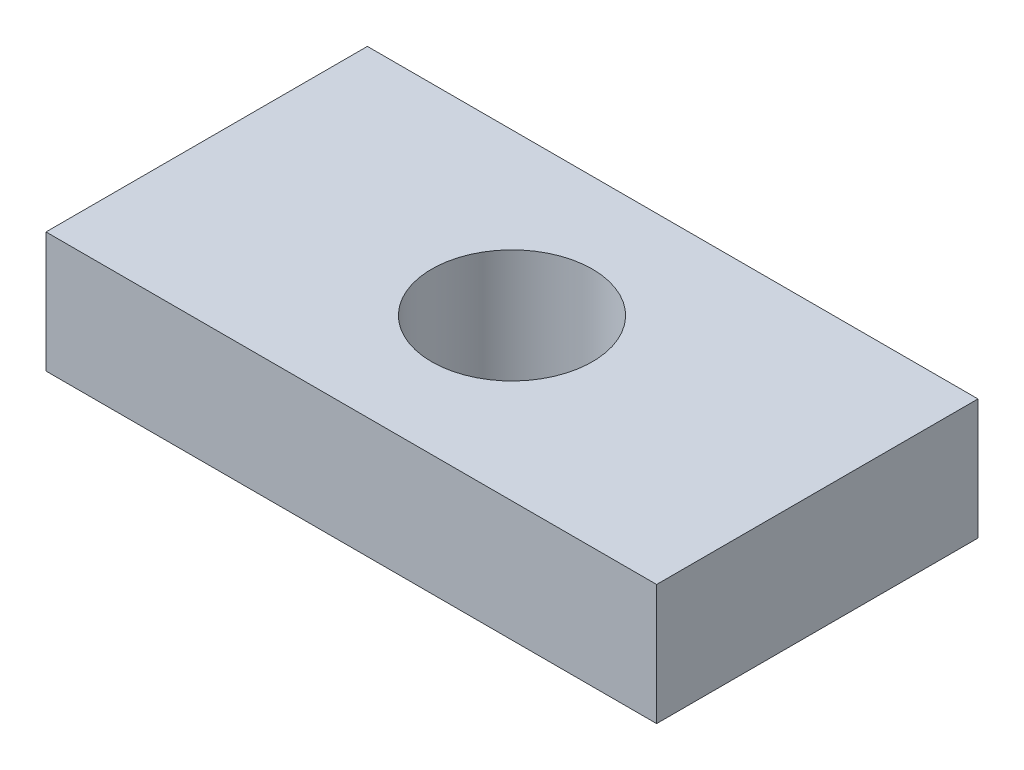
SolidWorks part; units mm, degrees
ref_plane "Front Plane" through (0, 0, 0) normal (0, 0, 1) x (1, 0, 0)
ref_plane "Top Plane" through (0, 0, 0) normal (0, 1, 0) x (1, 0, 0)
ref_plane "Right Plane" through (0, 0, 0) normal (1, 0, 0) x (0, 0, -1)
sketch "Sketch1" plane through (0, 0, 0) normal (0, 1, 0) x (1, 0, 0)
  line L1 (-38, 20) -> (38, 20)
  line L2 (-38, 20) -> (-38, -20)
  line L3 (-38, -20) -> (38, -20)
  line L4 (38, 20) -> (38, -20)
  line L5 (-38, 20) -> (38, -20) construction
  line L6 (-38, -20) -> (38, 20) construction
  circle A0 centre (0, 0) radius 10
  point P0 (0, 0)
extrude "Boss-Extrude1" add sketch "Sketch1" along normal blind 15
